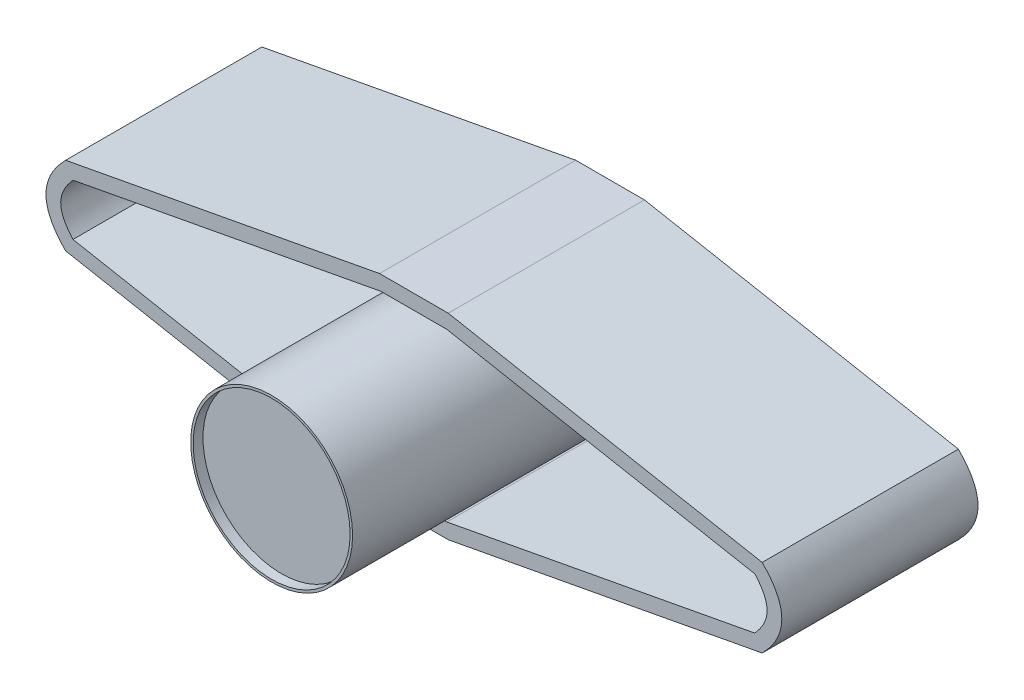
SolidWorks part; units mm, degrees
ref_plane "Front Plane" through (0, 0, 0) normal (0, 0, 1) x (1, 0, 0)
ref_plane "Top Plane" through (0, 0, 0) normal (0, 1, 0) x (1, 0, 0)
ref_plane "Right Plane" through (0, 0, 0) normal (1, 0, 0) x (0, 0, -1)
sketch "Sketch1" plane through (0, 0, 0) normal (0, 0, 1) x (1, 0, 0)
  line L0 (37.5, 0) -> (-37.5, 0) construction
  line L1 (-37.5, 10) -> (37.5, 10) construction
  line L2 (-37.5, 10) -> (-37.5, -10) construction
  line L3 (-37.5, -10) -> (37.5, -10) construction
  line L4 (37.5, 10) -> (37.5, -10) construction
  line L5 (-37.5, 10) -> (37.5, -10) construction
  line L6 (-37.5, -10) -> (37.5, 10) construction
  line L7 (0, 10) -> (0, -10) construction
  line L8 (0, -10) -> (-0.2433, -10.2385) construction
  line L9 (3.5, 10) -> (3.5, -10) construction
  line L10 (-37.5, 4) -> (37.5, 4) construction
  line L11 (37.5, -4) -> (-37.5, -4) construction
  line L12 (3.5, -10) -> (3.2917, -10.1258) construction
  line L13 (-3.5, 10) -> (-3.5, -10) construction
  line L14 (-35.5, 10) -> (-35.5, -10) construction
  line L15 (35.5, 10) -> (35.5, -10) construction
  line L16 (-35.5, 4) -> (-3.5, 10)
  line L17 (-3.5, 10) -> (3.5, 10)
  line L18 (3.5, 10) -> (35.5, 4)
  line L19 (35.5, -4) -> (3.5, -10)
  line L20 (3.5, -10) -> (-3.5, -10)
  line L21 (-3.5, -10) -> (-35.5, -4)
  spline S0 degree 2 poles (-35.5, 4) (-39.5, 0) (-35.5, -4) knots 0 0 0 1 1 1
  spline S1 degree 2 poles (35.5, 4) (39.5, 0) (35.5, -4) knots 0 0 0 1 1 1
  point P0 (0, 0)
  point P9 (37.5, -8.5)
  point P10 (37.5, 4)
  point P11 (37.5, -4)
  point P23 (-3.5, 10)
  point P24 (3.5, 10)
  dimension "D1" = 75
  dimension "D2" = 2
  dimension "D3" = 2
extrude "Boss-Extrude1" add sketch "Sketch1" along normal blind 20
shell "Shell2" thickness 1.5
sketch "Sketch4" plane through (0, 0, 1.5) normal (0, 0, 1) x (1, 0, 0)
  circle A0 centre (0, 0) radius 8.25
  dimension "D1" = 16.5
extrude "Boss-Extrude6" add sketch "Sketch4" along normal blind 33
sketch "Sketch5" plane through (0, 0, 34.5) normal (0, 0, 1) x (1, 0, 0)
  circle A0 centre (0, 0) radius 8
  dimension "D1" = 16
extrude "Cut-Extrude1" cut sketch "Sketch5" against normal blind 1
